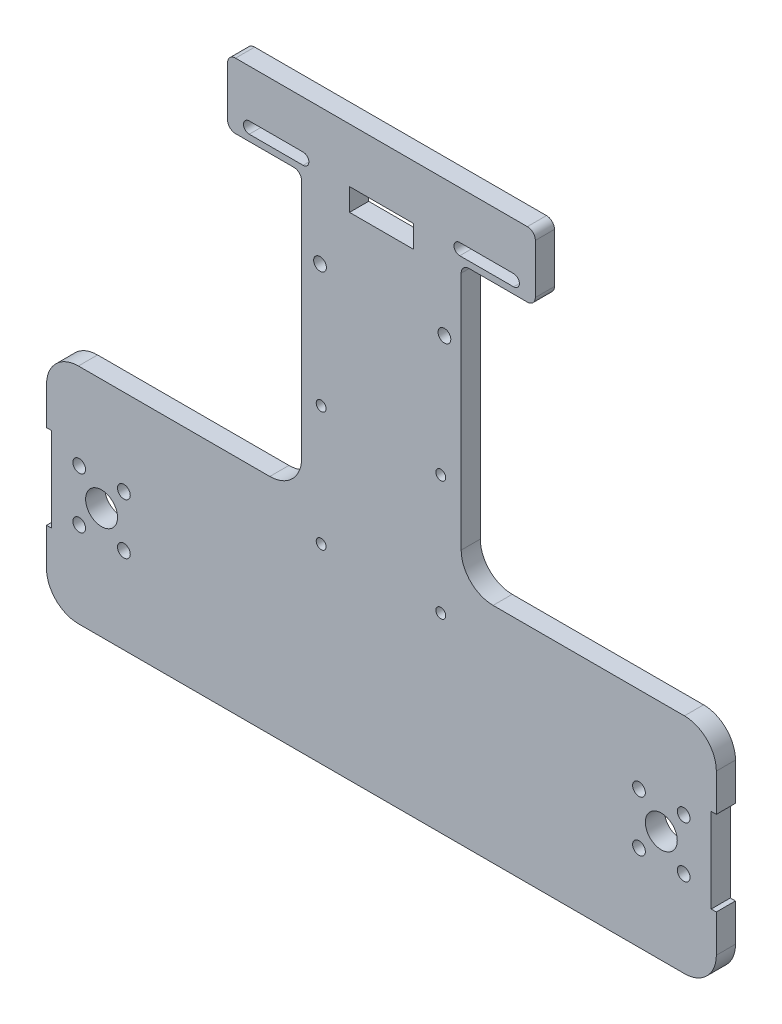
SolidWorks part; units mm, degrees
material "Acrylic (Medium-high impact)"
ref_plane "Front Plane" through (0, 0, 0) normal (0, 0, 1) x (1, 0, 0)
ref_plane "Top Plane" through (0, 0, 0) normal (0, 1, 0) x (1, 0, 0)
ref_plane "Right Plane" through (0, 0, 0) normal (1, 0, 0) x (0, 0, -1)
sketch "Sketch1" plane through (0, 0, 0) normal (0, 0, 1) x (1, 0, 0)
  line L0 (-41.45, 49.205) -> (-24.55, 49.205)
  line L1 (-24.55, 45.605) -> (-41.45, 45.605)
  line L2 (41.45, 45.605) -> (24.55, 45.605)
  line L3 (24.55, 49.205) -> (41.45, 49.205)
  line L4 (-10, 47.105) -> (10, 47.105)
  line L5 (-10, 40.105) -> (-10, 47.105)
  line L6 (10, 40.105) -> (-10, 40.105)
  line L7 (10, 47.105) -> (10, 40.105)
  line L8 (95, -44.105) -> (35, -44.105)
  line L9 (105, -65.855) -> (105, -54.105)
  line L10 (103.4, -65.855) -> (105, -65.855)
  line L11 (103.4, -92.355) -> (103.4, -65.855)
  line L12 (105, -92.355) -> (103.4, -92.355)
  line L13 (105, -104.105) -> (105, -92.355)
  line L14 (-95, -114.105) -> (95, -114.105)
  line L15 (-105, -92.355) -> (-105, -104.105)
  line L16 (-103.4, -92.355) -> (-105, -92.355)
  line L17 (-103.4, -65.855) -> (-103.4, -92.355)
  line L18 (-105, -65.855) -> (-103.4, -65.855)
  line L19 (-105, -54.105) -> (-105, -65.855)
  line L20 (-35, -44.105) -> (-95, -44.105)
  line L21 (-25, 41.105) -> (-25, -34.105)
  line L22 (-45.75, 43.605) -> (-27.5, 43.605)
  line L23 (-48.25, 61.605) -> (-48.25, 46.105)
  line L24 (45.75, 64.105) -> (-45.75, 64.105)
  line L25 (48.25, 46.105) -> (48.25, 61.605)
  line L26 (27.5, 43.605) -> (45.75, 43.605)
  line L27 (25, -34.105) -> (25, 41.105)
  circle A0 centre (80.75, -87.105) radius 2
  circle A1 centre (87.75, -79.105) radius 5
  circle A2 centre (94.75, -71.105) radius 2
  circle A3 centre (80.75, -71.105) radius 2
  circle A4 centre (-80.75, -71.105) radius 2
  circle A5 centre (-94.75, -71.105) radius 2
  circle A6 centre (-87.75, -79.105) radius 5
  circle A7 centre (-80.75, -87.105) radius 2
  circle A8 centre (-18.8943, -54.3781) radius 1.55
  circle A9 centre (18.6057, -16.8781) radius 1.55
  circle A10 centre (-18.8943, -16.8781) radius 1.55
  circle A11 centre (18.6057, -54.3781) radius 1.55
  circle A12 centre (19.7467, 21.4881) radius 2
  circle A13 centre (-19.2533, 21.4881) radius 2
  circle A14 centre (-94.75, -87.105) radius 2
  circle A15 centre (94.75, -87.105) radius 2
  arc A16 (-41.45, 49.205) -> (-41.45, 45.605) centre (-41.45, 47.405) ccw
  arc A17 (-24.55, 45.605) -> (-24.55, 49.205) centre (-24.55, 47.405) ccw
  arc A18 (41.45, 45.605) -> (41.45, 49.205) centre (41.45, 47.405) ccw
  arc A19 (24.55, 49.205) -> (24.55, 45.605) centre (24.55, 47.405) ccw
  arc A20 (105, -54.105) -> (95, -44.105) centre (95, -54.105) ccw
  arc A21 (95, -114.105) -> (105, -104.105) centre (95, -104.105) ccw
  arc A22 (-105, -104.105) -> (-95, -114.105) centre (-95, -104.105) ccw
  arc A23 (-95, -44.105) -> (-105, -54.105) centre (-95, -54.105) ccw
  arc A24 (-35, -44.105) -> (-25, -34.105) centre (-35, -34.105) ccw
  arc A25 (25, -34.105) -> (35, -44.105) centre (35, -34.105) ccw
  arc A26 (27.5, 43.605) -> (25, 41.105) centre (27.5, 41.105) ccw
  arc A27 (-25, 41.105) -> (-27.5, 43.605) centre (-27.5, 41.105) ccw
  arc A28 (45.75, 43.605) -> (48.25, 46.105) centre (45.75, 46.105) ccw
  arc A29 (48.25, 61.605) -> (45.75, 64.105) centre (45.75, 61.605) ccw
  arc A30 (-45.75, 43.605) -> (-48.25, 46.105) centre (-45.75, 46.105) cw
  arc A31 (-48.25, 61.605) -> (-45.75, 64.105) centre (-45.75, 61.605) cw
  point P89 (48.25, 43.605)
  point P92 (48.25, 64.105)
  dimension "D8" = 2.5
  dimension "D1" = 3.8
  dimension "D2" = 0.3
  dimension "D3" = 20
  dimension "D4" = 7
  dimension "D5" = 17
  dimension "D6" = 20.5
  dimension "D7" = 18.6169
extrude "Boss-Extrude1" add sketch "Sketch1" along normal blind 6
